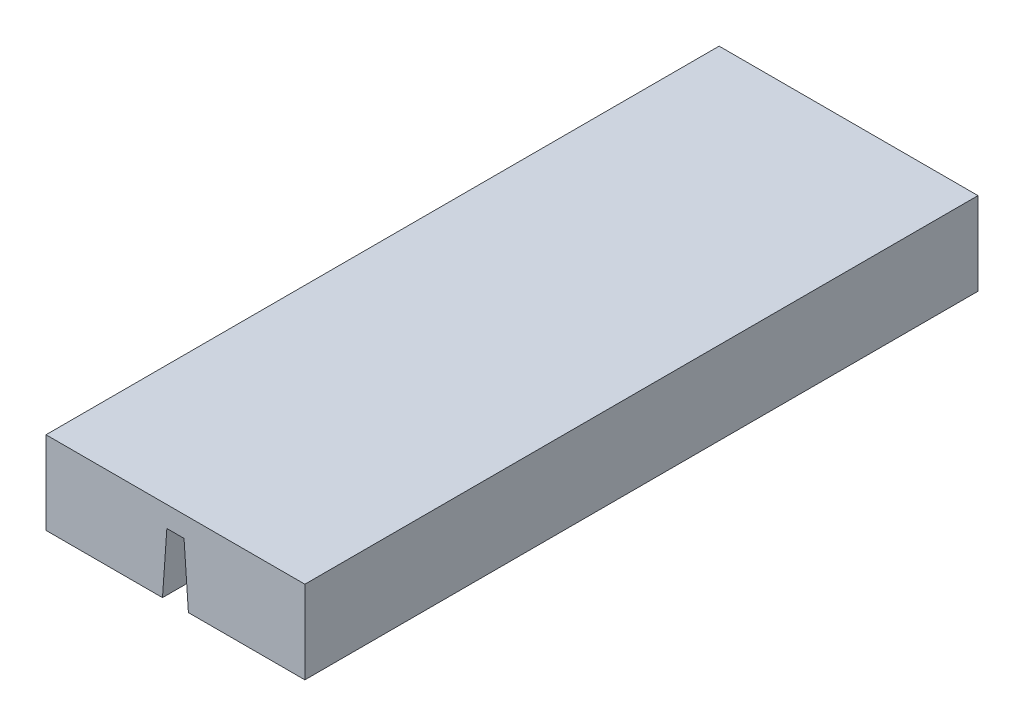
SolidWorks part; units mm, degrees
ref_plane "Front Plane" through (0, 0, 0) normal (0, 0, 1) x (1, 0, 0)
ref_plane "Top Plane" through (0, 0, 0) normal (0, 1, 0) x (1, 0, 0)
ref_plane "Right Plane" through (0, 0, 0) normal (1, 0, 0) x (0, 0, -1)
sketch "Sketch1" plane through (0, 0, 0) normal (0, 1, 0) x (1, 0, 0)
  line L1 (0, 0) -> (50, 0)
  line L2 (0, 0) -> (0, -130)
  line L3 (0, -130) -> (50, -130)
  line L4 (50, 0) -> (50, -130)
  dimension "D1" = 50
  dimension "D2" = 130
extrude "Boss-Extrude1" add sketch "Sketch1" along normal blind 16
sketch "Sketch3" plane through (0, 0, 130) normal (0, 0, 1) x (1, 0, 0)
  line L0 (50, 0) -> (50, 12)
  line L1 (50, 16) -> (50, 0) construction
  line L3 (0, 0) -> (50, 0) construction
  line L5 (0, 0) -> (0, 12)
  line L6 (22.5, 0) -> (27.5, 0)
  line L9 (22.5, 0) -> (23.3388, 11.9953)
  line L10 (27.5, 0) -> (26.6612, 11.9953)
  line L11 (23.3388, 11.9953) -> (26.6612, 11.9953)
  dimension "D1" = 12
  dimension "D3" = 4
extrude "Cut-Extrude1" cut sketch "Sketch3" against normal blind 167 contours L11 L10 L6 L9
